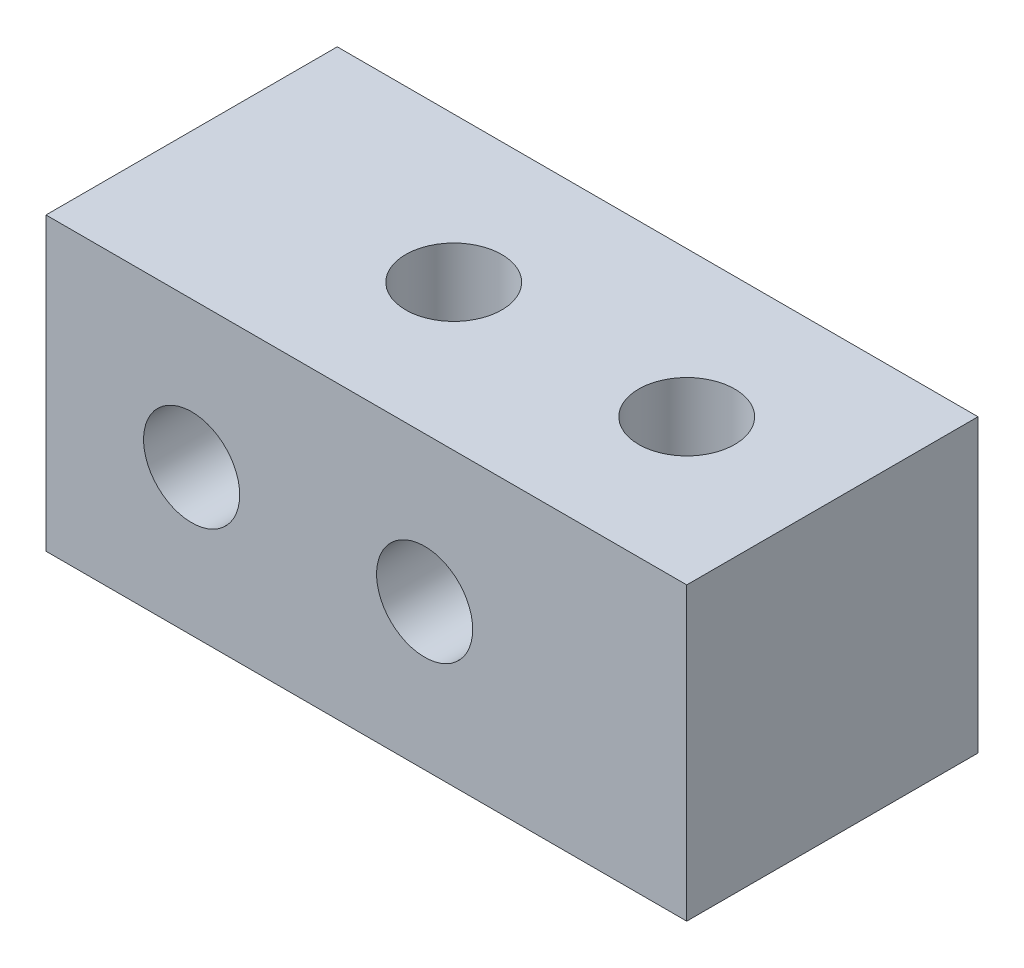
SolidWorks part; units mm, degrees
material "6061 合金"
ref_plane "前视基准面" through (0, 0, 0) normal (0, 0, 1) x (1, 0, 0)
ref_plane "上视基准面" through (0, 0, 0) normal (0, 1, 0) x (1, 0, 0)
ref_plane "右视基准面" through (0, 0, 0) normal (1, 0, 0) x (0, 0, -1)
sketch "草图1" plane through (0, 0, 0) normal (0, 0, 1) x (1, 0, 0)
  line L1 (11, -5) -> (-11, -5)
  line L2 (11, -5) -> (11, 5)
  line L3 (11, 5) -> (-11, 5)
  line L4 (-11, -5) -> (-11, 5)
  line L5 (11, -5) -> (-11, 5) construction
  line L6 (11, 5) -> (-11, -5) construction
  point P0 (0, 0)
  dimension "D1" = 22
  dimension "D2" = 10
extrude "凸台-拉伸1" add sketch "草图1" along normal blind 10
sketch "草图2" plane through (0, 0, 10) normal (0, 0, 1) x (1, 0, 0)
  line L0 (-11, 5) -> (-11, -5) construction
  point P0 (-6, 0)
  point P1 (2, 0)
  point P6 (-16.4701, 13.3951)
  dimension "D1" = 5
  dimension "D2" = 8
sketch "草图3" plane through (0, 5, 0) normal (0, 1, 0) x (1, 0, 0)
  line L0 (11, -10) -> (11, 0) construction
  point P0 (-2, -5)
  point P1 (6, -5)
  dimension "D1" = 5
  dimension "D2" = 8
hole_wizard "M4 螺纹孔的螺纹孔钻头1" positions "3D草图1" profile "草图4" hole size "M4" standard "DIN" end condition through all
sketch3d "3D草图1"
  point P0 (-6, 0, 10)
  point P3 (2, 0, 10)
  point P6 (-2, 5, 5)
  point P9 (6, 5, 5)
sketch "草图4" plane through (-6, 0, 10) normal (1, 0, 0) x (0, -1, 0)
  line L0 (0, 0) -> (0, 10)
  line L1 (0, 10) -> (1.65, 10)
  line L2 (1.65, 10) -> (1.65, 0)
  line L5 (1.65, 0) -> (0, 0)
  line L11 (0, -6.35) -> (0, 107.95) construction
  dimension "通孔孔直径" = 3.3
  dimension "通孔孔深度" = 10
